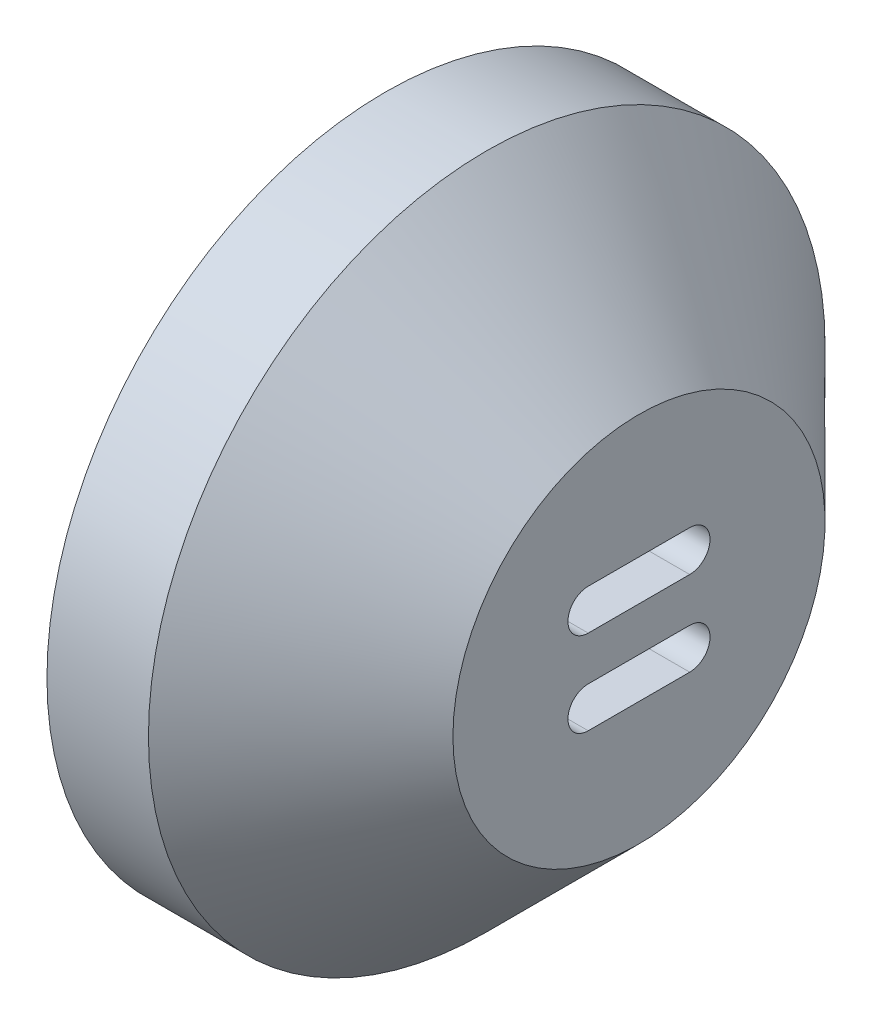
SolidWorks part; units mm, degrees
ref_plane "Front Plane" through (0, 0, 0) normal (0, 0, 1) x (1, 0, 0)
ref_plane "Top Plane" through (0, 0, 0) normal (0, 1, 0) x (1, 0, 0)
ref_plane "Right Plane" through (0, 0, 0) normal (1, 0, 0) x (0, 0, -1)
sketch "Sketch1" plane through (0, 0, 0) normal (0, 0, 1) x (1, 0, 0)
  line L0 (0, 43.8976) -> (30, 43.8976)
  line L1 (30, 43.8976) -> (75, -1.1024)
  line L2 (75, -1.1024) -> (75, -56.1024)
  line L3 (0, 31.8976) -> (25.0294, 31.8976)
  line L4 (25.0294, 31.8976) -> (63, -6.0729)
  line L5 (63, -6.0729) -> (63, -56.1024)
  line L6 (0, 43.8976) -> (0, 31.8976)
  line L7 (63, -56.1024) -> (75, -56.1024)
  dimension "D1" = 75
  dimension "D2" = 45
  dimension "D3" = 55
  dimension "D4" = 100
  dimension "D5" = 12
revolve "Revolve" add sketch "Sketch1" angle 360 about L7
sketch "Sketch2" plane through (63, 0, 0) normal (-1, 0, 0) x (0, 0, 1)
  line L0 (-100, -56.1024) -> (100, -56.1024) construction
  line L1 (0, 43.8976) -> (0, 31.8976) construction
  line L2 (-15, -43.6024) -> (15, -43.6024) construction
  line L3 (-15, -37.6024) -> (15, -37.6024)
  line L4 (-15, -49.6024) -> (15, -49.6024)
  line L5 (0, -56.1024) -> (0, 43.8976) construction
  circle A0 centre (0, -56.1024) radius 100 construction
  circle A1 centre (0, -56.1024) radius 88 construction
  circle A2 centre (0, -56.1024) radius 94 construction
  arc A3 (-15, -37.6024) -> (-15, -49.6024) centre (-15, -43.6024) ccw
  arc A4 (15, -49.6024) -> (15, -37.6024) centre (15, -43.6024) ccw
  point P10 (0, 37.8976)
  point P15 (0, -43.6024)
  dimension "D1" = 30
  dimension "D2" = 12.5
  dimension "D3" = 12
hole_wizard "M8x1.0 Tapped Hole" positions "Sketch4" profile "Sketch3" tap size "M8x1.0" standard "ANSI Metric"
sketch "Sketch4" plane through (0, 0, 0) normal (-1, 0, 0) x (0, 0, 1)
  point P0 (0, 37.8976)
sketch "Sketch3" plane through (0, 37.8976, 0) normal (0, 1, 0) x (0, 0, 1)
  line L0 (0, 0) -> (0, 23.103)
  line L1 (0, 23.103) -> (3.5, 21)
  line L2 (3.5, 21) -> (3.5, 0)
  line L5 (3.5, 0) -> (0, 0)
  line L10 (0, 23.103) -> (-3.5, 21) construction
  line L11 (0, -6.35) -> (0, 107.95) construction
  dimension "Tap Drill Dia." = 7
  dimension "Tap Drill Depth" = 21
  dimension "Drill Angle" = 118
cosmetic thread "Hole Thread1" parameters "D1"=16, "D2"=8
pattern_circular "CirPattern" count 8 over 360 about axis through (0, -56.1024, 0) along (1, 0, 0) of "M8x1.0 Tapped Hole"
extrude "Slot Cut" cut sketch "Sketch2" against normal through all
sketch "Sketch" plane through (63, 0, 0) normal (-1, 0, 0) x (0, 0, 1)
  line L0 (-100, -56.1024) -> (100, -56.1024) construction
  circle A0 centre (0, -56.1024) radius 100 construction
ref_plane "Plane" through (0, -56.1024, 0) normal (0, 1, 0) x (1, 0, 0)
mirror "Mirror" about plane through (0, -56.1024, 0) normal (0, 1, 0) of "Slot Cut"
